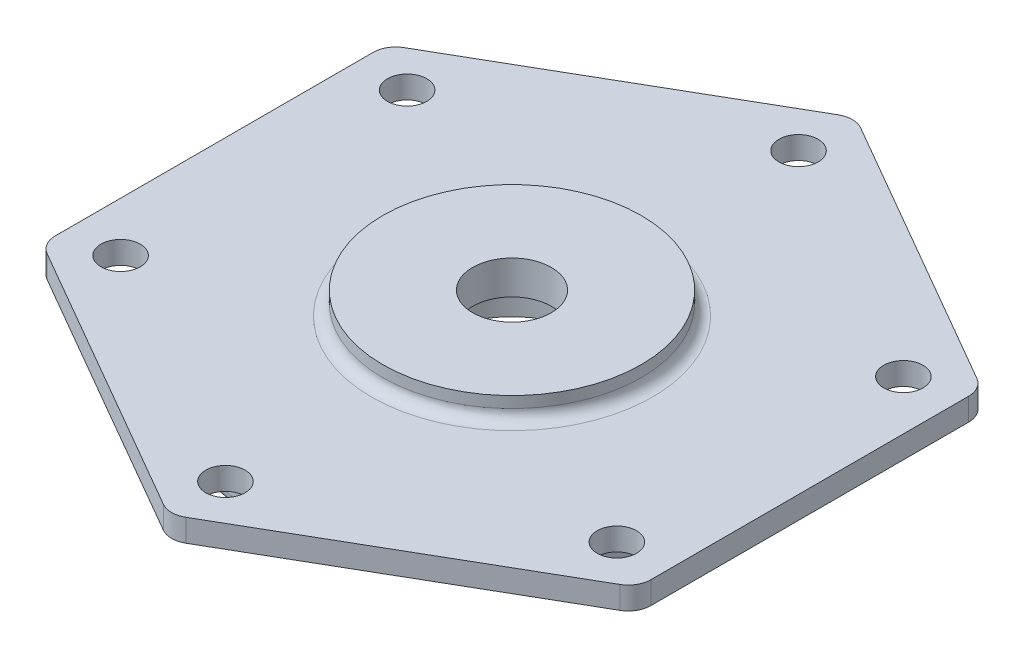
SolidWorks part; units mm, degrees
ref_plane "Front Plane" through (0, 0, 0) normal (0, 0, 1) x (1, 0, 0)
ref_plane "Top Plane" through (0, 0, 0) normal (0, 1, 0) x (1, 0, 0)
ref_plane "Right Plane" through (0, 0, 0) normal (1, 0, 0) x (0, 0, -1)
sketch "Sketch1" plane through (0, 0, 0) normal (0, 1, 0) x (1, 0, 0)
  line L1 (-2, 60.0444) -> (-51, 31.7543)
  line L2 (-53, 28.2902) -> (-53, -28.2902)
  line L3 (-51, -31.7543) -> (-2, -60.0444)
  line L4 (2, -60.0444) -> (51, -31.7543)
  line L5 (53, -28.2902) -> (53, 28.2902)
  line L6 (51, 31.7543) -> (2, 60.0444)
  circle A0 centre (0, 0) radius 53 construction
  arc A1 (53, 28.2902) -> (51, 31.7543) centre (49, 28.2902) ccw
  arc A2 (51, -31.7543) -> (53, -28.2902) centre (49, -28.2902) ccw
  arc A3 (-2, -60.0444) -> (2, -60.0444) centre (0, -56.5803) ccw
  arc A4 (-53, -28.2902) -> (-51, -31.7543) centre (-49, -28.2902) ccw
  arc A5 (-51, 31.7543) -> (-53, 28.2902) centre (-49, 28.2902) ccw
  arc A6 (-2, 60.0444) -> (2, 60.0444) centre (0, 56.5803) cw
  dimension "D2" = 4
  dimension "D1" = 106
extrude "Boss-Extrude1" add sketch "Sketch1" along normal blind 4
sketch "Sketch2" plane through (0, 4, 0) normal (0, 1, 0) x (1, 0, 0)
  circle A0 centre (0, 0) radius 23
extrude "Boss-Extrude2" add sketch "Sketch2" along normal blind 4
sketch "Sketch3" plane through (0, 0, 0) normal (0, -1, 0) x (1, 0, 0)
  circle A0 centre (0, 0) radius 45
extrude "Boss-Extrude3" add sketch "Sketch3" along normal blind 6
sketch "Sketch4" plane through (0, -6, 0) normal (0, -1, 0) x (-1, 0, 0)
  circle A0 centre (0, 0) radius 40
  circle A1 centre (0, 0) radius 19
extrude "Cut-Extrude1" cut sketch "Sketch4" against normal blind 6
sketch "Sketch5" plane through (0, -6, 0) normal (0, -1, 0) x (1, 0, 0)
  circle A0 centre (0, 0) radius 14
extrude "Cut-Extrude2" cut sketch "Sketch5" against normal blind 8
sketch "Sketch6" plane through (0, 2, 0) normal (0, -1, 0) x (-1, 0, 0)
  circle A0 centre (0, 0) radius 7
extrude "Cut-Extrude3" cut sketch "Sketch6" against normal through all
fillet "Fillet2" radius 2 3 edges at (0, 4, 23) (0, -6, -45) (0, -6, -19)
sketch "Sketch7" plane through (0, 4, 0) normal (0, 1, 0) x (1, 0, 0)
  circle A0 centre (0, 0) radius 51 construction
  circle A1 centre (0, 51) radius 3.5
  circle A2 centre (44.1673, 25.5) radius 3.5
  circle A3 centre (44.1673, -25.5) radius 3.5
  circle A4 centre (0, -51) radius 3.5
  circle A5 centre (-44.1673, -25.5) radius 3.5
  circle A6 centre (-44.1673, 25.5) radius 3.5
  point P17 (0, 0)
  dimension "D1" = 6
extrude "Cut-Extrude4" cut sketch "Sketch7" against normal through all
